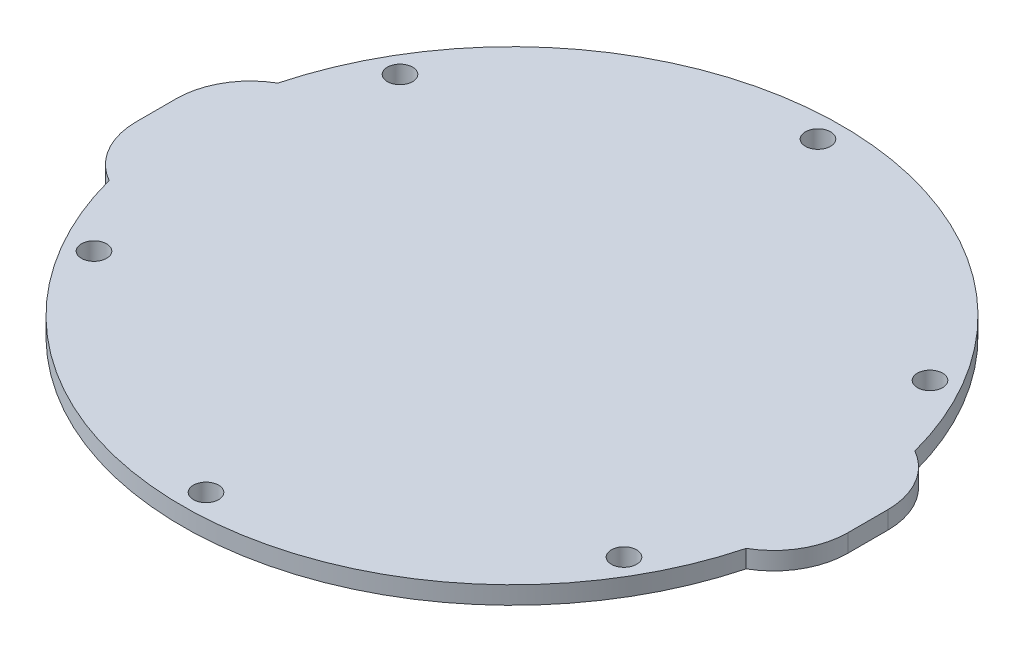
SolidWorks part; units mm, degrees
material "1060 Alloy"
ref_plane "Front Plane" through (0, 0, 0) normal (0, 0, 1) x (1, 0, 0)
ref_plane "Top Plane" through (0, 0, 0) normal (0, 1, 0) x (1, 0, 0)
ref_plane "Right Plane" through (0, 0, 0) normal (1, 0, 0) x (0, 0, -1)
sketch "Sketch1" plane through (0, 0, 0) normal (0, 1, 0) x (1, 0, 0)
  line L0 (-48, 0) -> (48, 0) construction
  line L1 (-38, 12.7) -> (38, 12.7)
  line L2 (-48, 2.7) -> (-48, -2.7)
  line L3 (-38, -12.7) -> (38, -12.7)
  line L4 (48, 2.7) -> (48, -2.7)
  line L5 (0, 12.7) -> (0, -12.7) construction
  circle A0 centre (0, 0) radius 44.45
  arc A1 (38, -12.7) -> (48, -2.7) centre (38, -2.7) ccw
  arc A2 (38, 12.7) -> (48, 2.7) centre (38, 2.7) cw
  arc A3 (-38, 12.7) -> (-48, 2.7) centre (-38, 2.7) ccw
  arc A4 (-38, -12.7) -> (-48, -2.7) centre (-38, -2.7) cw
  point P11 (0, 0)
  point P18 (-48, 12.7)
  point P21 (-48, -12.7)
  dimension "D1" = 88.9
  dimension "D2" = 48
  dimension "D4" = 10
  dimension "D3" = 25.4
extrude "Boss-Extrude1" add sketch "Sketch1" along normal blind 2.4 contours A4 A0 A3 L2 | A4 L3 A1 A0 A2 L1 A3 | L3 A4 A0 A1 | A3 L1 A2 A0 | A2 A0 A1 L4
sketch "Sketch2" plane through (0, 2.4, 0) normal (0, 1, 0) x (1, 0, 0)
  circle A0 centre (0, 0) radius 41.275 construction
  dimension "D1" = 82.55
hole_wizard "M3 Clearance Hole1" positions "3DSketch2" profile "Sketch4" hole size "M3" standard "ANSI Metric" end condition through all
sketch3d "3DSketch2"
  line L0 (0, 2.4, -41.275) -> (0, 2.4, 41.275) construction
  line L2 (-41.275, 2.4, 0) -> (41.275, 2.4, 0) construction
  circle A0 centre (0, 2.4, 0) radius 41.275 construction
  point P0 (0, 2.4, -41.275)
  point P4 (0, 43.675, 0)
  point P15 (0, 2.4, 0)
  point P16 (0, 2.4, 0)
sketch "Sketch4" plane through (0, 2.4, -41.275) normal (1, 0, 0) x (0, 0, 1)
  line L0 (0, 0) -> (0, 2.4)
  line L1 (0, 2.4) -> (1.7, 2.4)
  line L2 (1.7, 2.4) -> (1.7, 0)
  line L5 (1.7, 0) -> (0, 0)
  line L11 (0, -6.35) -> (0, 107.95) construction
  dimension "Thru Hole Dia." = 3.4
  dimension "Thru Hole Depth" = 2.4
pattern_circular "CirPattern1" count 6 over 360 about axis through (0, 0, 0) along (0, 1, 0) of "M3 Clearance Hole1"
